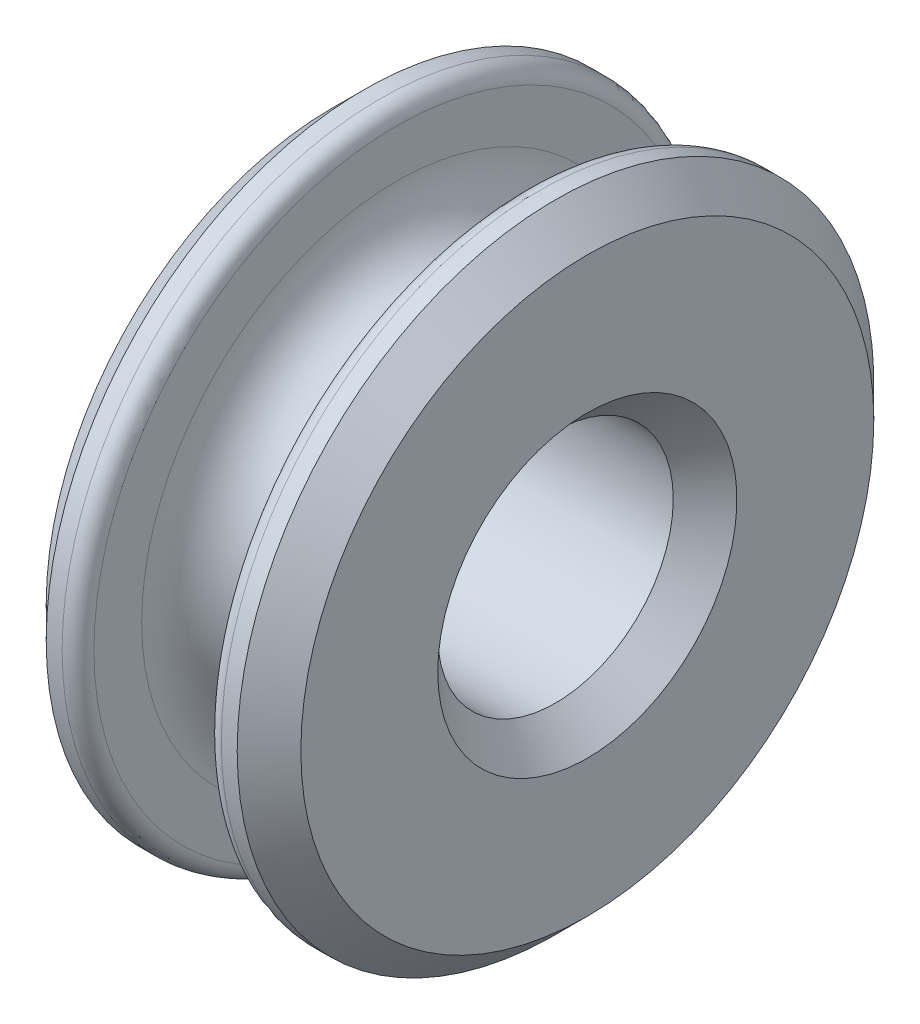
SolidWorks part; units mm, degrees
material "Nylon 101"
ref_plane "Front" through (0, 0, 0) normal (0, 0, 1) x (1, 0, 0)
ref_plane "Top" through (0, 0, 0) normal (0, 1, 0) x (1, 0, 0)
ref_plane "Right" through (0, 0, 0) normal (1, 0, 0) x (0, 0, -1)
sketch "Sketch1" plane through (0, 0, 0) normal (0, 0, 1) x (1, 0, 0)
  line L0 (0, 0) -> (2.2033, 0) construction
  line L1 (0, 5) -> (0, 1.85)
  line L2 (0, 1.85) -> (4, 1.85)
  line L3 (4, 1.85) -> (4, 5)
  line L4 (4, 5) -> (3, 5)
  line L5 (3, 5) -> (3, 4)
  line L7 (1, 4) -> (1, 5)
  line L8 (1, 5) -> (0, 5)
  arc A2 (1, 4) -> (3, 4) centre (2, 4) ccw
  dimension "D1" = 3.7
  dimension "D4" = 8
  dimension "D2" = 1
  dimension "D3" = 4
  dimension "D5" = 10
revolve "Revolve1" add sketch "Sketch1" angle 360 about L0
fillet "Fillet1" radius 0.25 2 edges at (3, 0, 5) (1, 0, 5)
chamfer "Chamfer1" distance 0.5 angle 45 4 edges at (4, 0, 1.85) (4, 0, 5) (0, 0, 5) (0, 0, 1.85)
